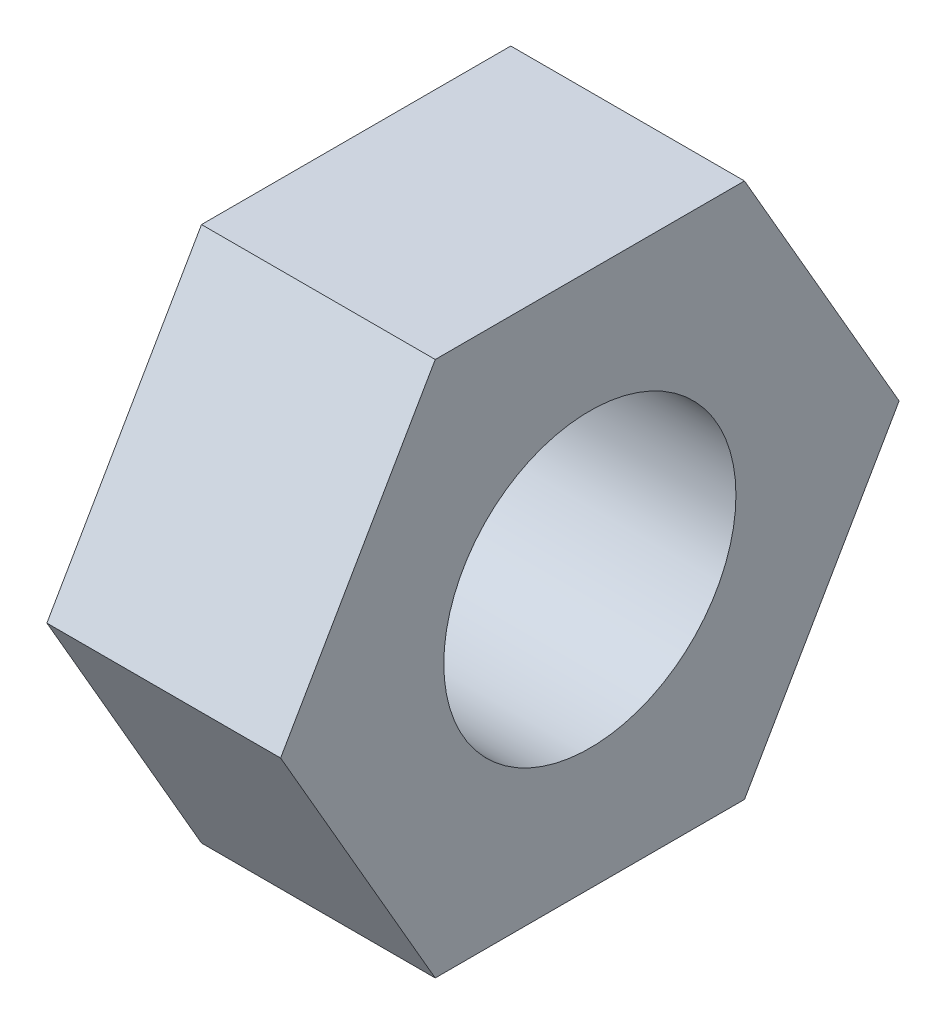
SolidWorks part; units mm, degrees
ref_plane "Front" through (0, 0, 0) normal (0, 0, 1) x (1, 0, 0)
ref_plane "Top" through (0, 0, 0) normal (0, 1, 0) x (1, 0, 0)
ref_plane "Right" through (0, 0, 0) normal (1, 0, 0) x (0, 0, -1)
sketch "Sketch1" plane through (0, 0, 0) normal (1, 0, 0) x (0, 0, -1)
  line L1 (3.1754, 0) -> (1.5877, 2.75)
  line L2 (1.5877, 2.75) -> (-1.5877, 2.75)
  line L3 (-1.5877, 2.75) -> (-3.1754, 0)
  line L4 (-3.1754, 0) -> (-1.5877, -2.75)
  line L5 (-1.5877, -2.75) -> (1.5877, -2.75)
  line L6 (1.5877, -2.75) -> (3.1754, 0)
  circle A0 centre (0, 0) radius 2.75 construction
  circle A1 centre (0, 0) radius 1.5
extrude "Boss-Extrude1" add sketch "Sketch1" along normal blind 2.4
